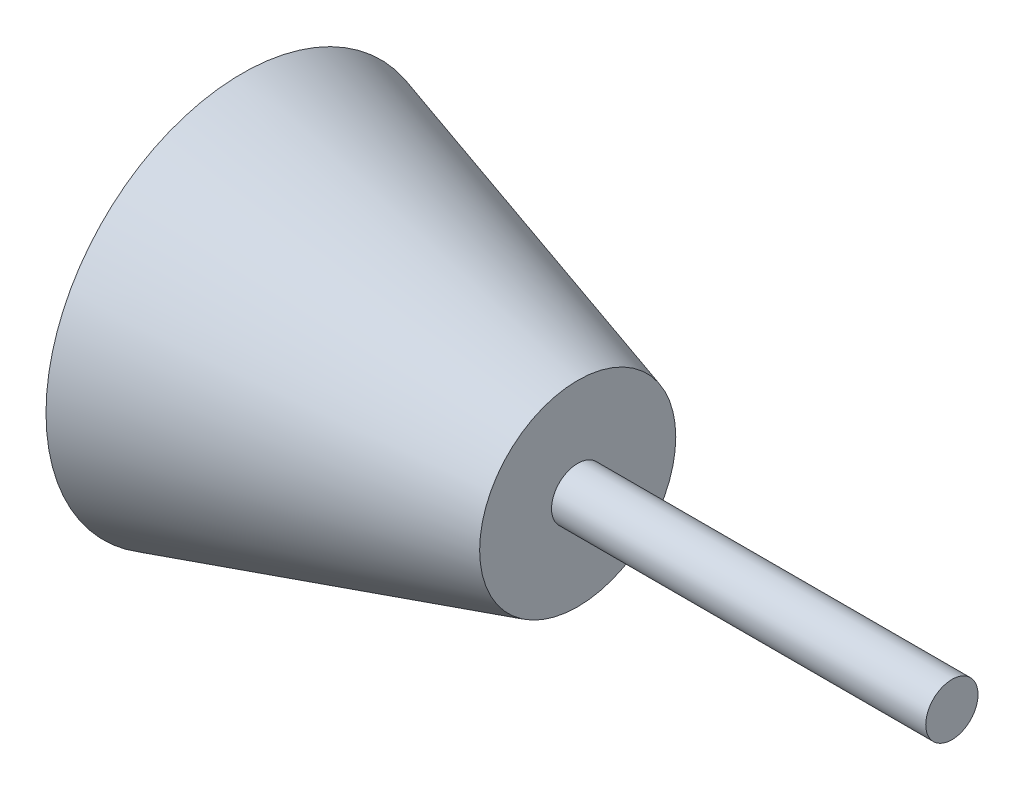
SolidWorks part; units mm, degrees
ref_plane "前视基准面" through (0, 0, 0) normal (0, 0, 1) x (1, 0, 0)
ref_plane "上视基准面" through (0, 0, 0) normal (0, 1, 0) x (1, 0, 0)
ref_plane "右视基准面" through (0, 0, 0) normal (1, 0, 0) x (0, 0, -1)
sketch "草图1" plane through (0, 0, 0) normal (0, 0, 1) x (1, 0, 0)
  line L0 (0, 0) -> (525, 0) construction
  line L1 (525, 0) -> (525, 890) construction
  line L2 (525, 890) -> (579.2797, 890) construction
  line L3 (525, 890) -> (525, 875)
  line L4 (525, 875) -> (550.6627, 882.5)
  line L6 (525, 890) -> (579.2797, 890)
  line L9 (550.6627, 882.5) -> (550.6627, 888)
  line L10 (550.6627, 888) -> (579.2797, 888)
  line L11 (579.2797, 888) -> (579.2797, 890)
  dimension "D1" = 525
  dimension "D2" = 890
  dimension "D3" = 15
  dimension "D4" = 2
  dimension "D5" = 7.5
revolve "旋转1" add sketch "草图1" angle 360 about L6
